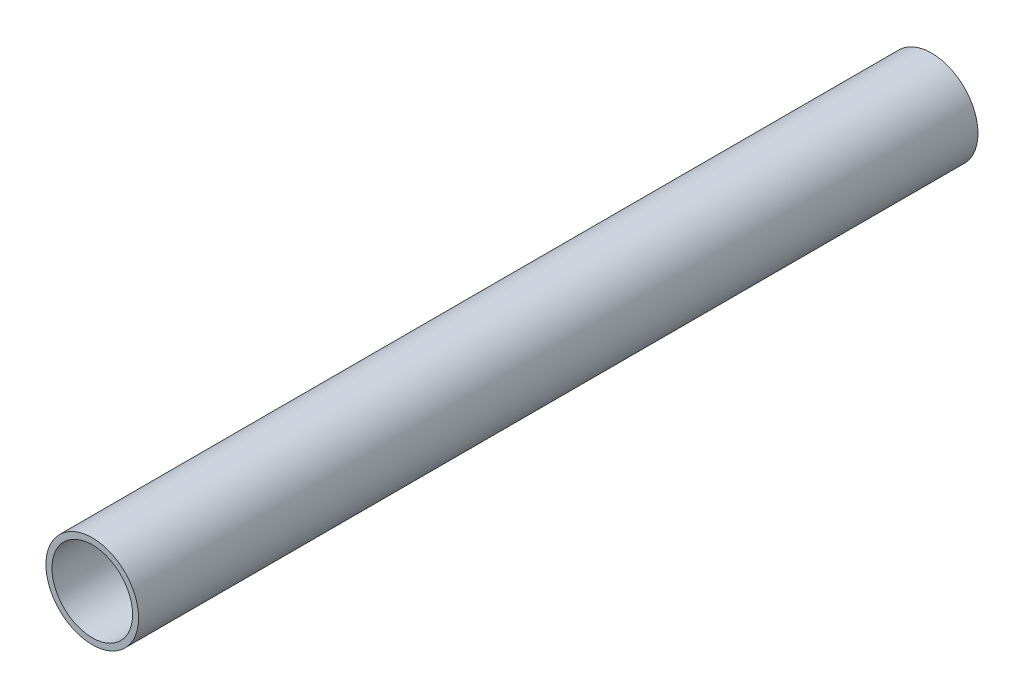
SolidWorks part; units mm, degrees
ref_plane "Front Plane" through (0, 0, 0) normal (0, 0, 1) x (1, 0, 0)
ref_plane "Top Plane" through (0, 0, 0) normal (0, 1, 0) x (1, 0, 0)
ref_plane "Right Plane" through (0, 0, 0) normal (1, 0, 0) x (0, 0, -1)
sketch "Sketch1" plane through (0, 0, 0) normal (0, 0, 1) x (1, 0, 0)
  circle A0 centre (0, 0) radius 84.1375
  dimension "Pipe OD" = 168.275
extrude "Extrude-Thin1" add sketch "Sketch1" along normal mid plane 1524 thin thin type one direction reverse wall 10.9728
